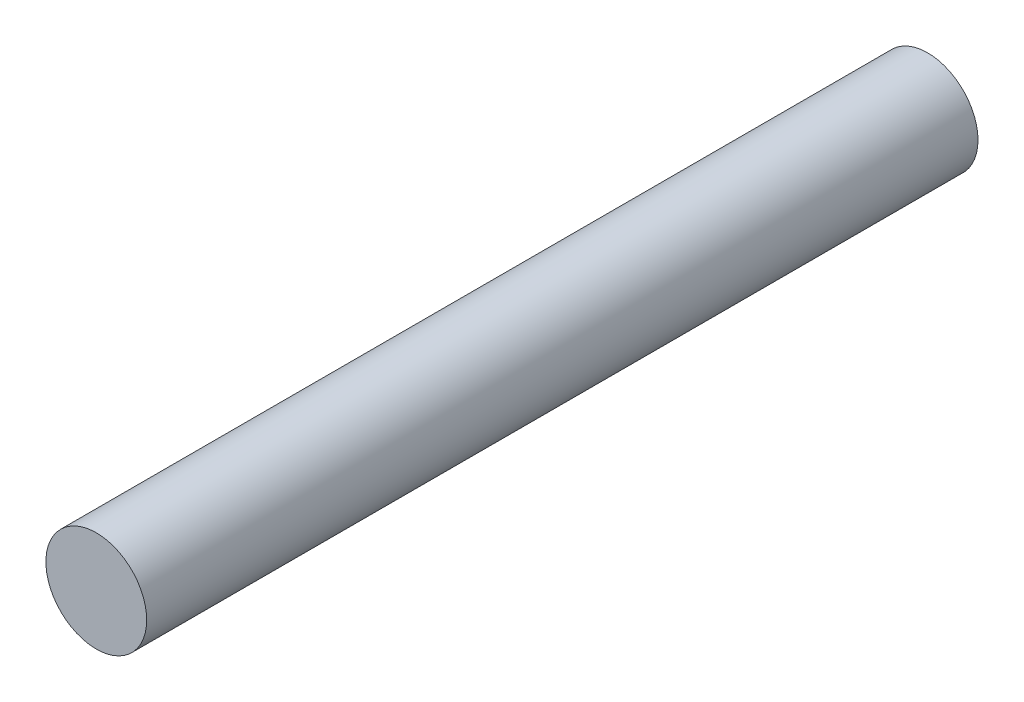
SolidWorks part; units mm, degrees
ref_plane "前视基准面" through (0, 0, 0) normal (0, 0, 1) x (1, 0, 0)
ref_plane "上视基准面" through (0, 0, 0) normal (0, 1, 0) x (1, 0, 0)
ref_plane "右视基准面" through (0, 0, 0) normal (1, 0, 0) x (0, 0, -1)
sketch "草图1" plane through (0, 0, 0) normal (0, 0, 1) x (1, 0, 0)
  circle A0 centre (0, 0) radius 4
extrude "凸台-拉伸1" add sketch "草图1" along normal blind 66
